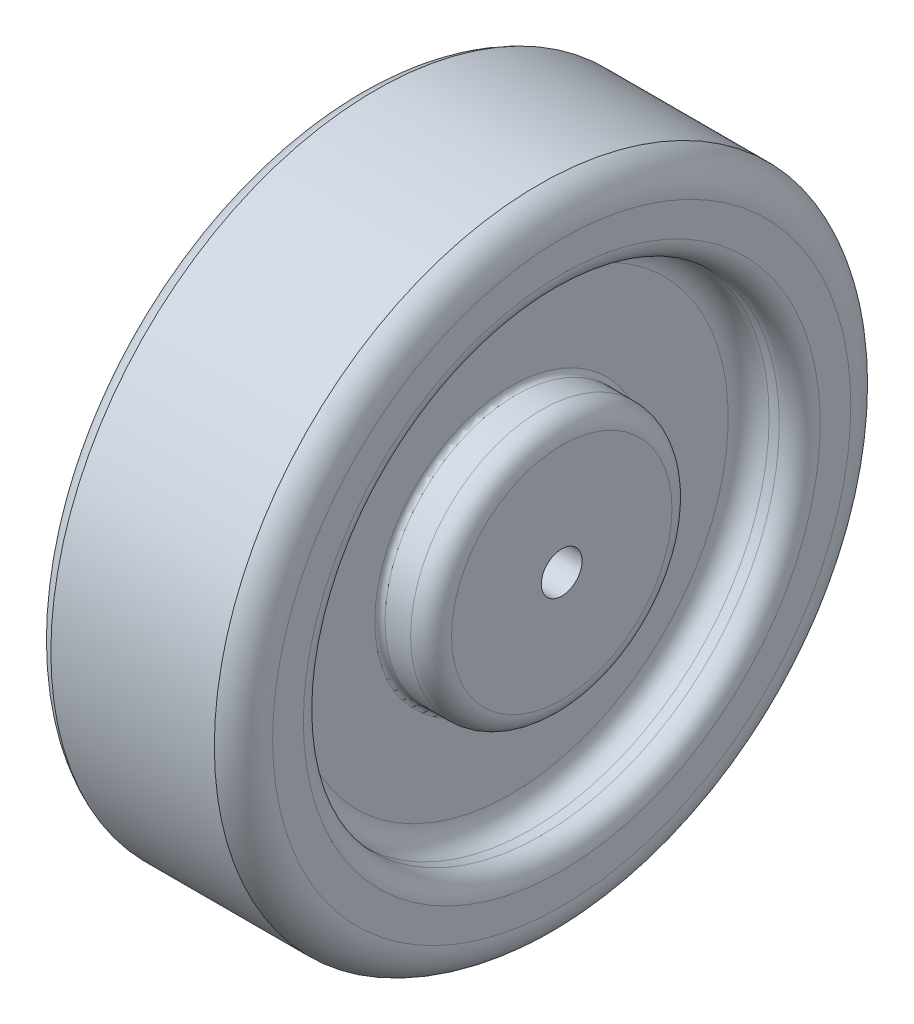
SolidWorks part; units mm, degrees
material "POLIURETANO RC (11671)"
ref_plane "Alzado" through (0, 0, 0) normal (0, 0, 1) x (1, 0, 0)
ref_plane "Planta" through (0, 0, 0) normal (0, 1, 0) x (1, 0, 0)
ref_plane "Vista lateral" through (0, 0, 0) normal (1, 0, 0) x (0, 0, -1)
sketch "Croquis3" plane through (0, 0, 0) normal (0, 1, 0) x (1, 0, 0)
  line L0 (20.5, 3.5822) -> (67.1331, 3.5822) construction
  line L1 (-20.5, 3.5822) -> (-65.0326, 3.5822) construction
  line L2 (-20.5, -2) -> (20.5, -2)
  line L3 (-20.5, 3.5822) -> (20.5, 3.5822) construction
  line L4 (-55, 0) -> (55, 0) construction
  line L6 (0, 3.5822) -> (0, -71.0271) construction
  line L7 (-20.5, -2) -> (-20.5, -17)
  line L8 (20.5, -48) -> (20.5, -47)
  line L9 (16.5, -43) -> (14.5, -43)
  line L10 (20.5, -17) -> (20.5, -18)
  line L11 (16.5, -22) -> (11.5, -22)
  line L12 (10.5, -23) -> (10.5, -39)
  line L14 (20.5, -2) -> (20.5, -17)
  line L15 (-10.5, -23) -> (-10.5, -39)
  line L16 (-16.5, -22) -> (-11.5, -22)
  line L17 (-20.5, -17) -> (-20.5, -18)
  line L18 (-16.5, -43) -> (-14.5, -43)
  line L19 (-20.5, -48) -> (-20.5, -47)
  line L20 (-20.5, -48) -> (-20.5, -53)
  line L22 (-16, -59.9178) -> (16, -59.9178)
  line L24 (20.5, -53) -> (20.5, -48)
  arc A0 (16.5, -43) -> (20.5, -47) centre (16.5, -47) cw
  arc A1 (10.5, -39) -> (14.5, -43) centre (14.5, -39) ccw
  arc A2 (11.5, -22) -> (10.5, -23) centre (11.5, -23) ccw
  arc A3 (20.5, -18) -> (16.5, -22) centre (16.5, -18) cw
  arc A4 (-20.5, -18) -> (-16.5, -22) centre (-16.5, -18) ccw
  arc A5 (-11.5, -22) -> (-10.5, -23) centre (-11.5, -23) cw
  arc A6 (-10.5, -39) -> (-14.5, -43) centre (-14.5, -39) cw
  arc A7 (-16.5, -43) -> (-20.5, -47) centre (-16.5, -47) ccw
  arc A8 (-16, -59.9178) -> (-20.5, -53) centre (-13.5101, -53.3756) cw
  arc A9 (16, -59.9178) -> (20.5, -53) centre (13.5101, -53.3756) ccw
  point P7 (0, -4)
  point P13 (0, -50)
  point P17 (0, -19)
  point P23 (20.5, -43)
  point P26 (10.5, -43)
  point P31 (-10.5, -43)
  point P32 (0, -2)
  point P45 (0, -50)
  point P46 (-20.5, -43)
  point P56 (0, -59.9178)
  dimension "D9" = 4
  dimension "D10" = 4
  dimension "D11" = 1
  dimension "D12" = 4
  dimension "D2" = 2
  dimension "D3" = 5
  dimension "D4" = 63.5
  dimension "D5" = 15
  dimension "D6" = 1
  dimension "D7" = 5
  dimension "D8" = 10
  dimension "D13" = 5
revolve "Revolución1" add sketch "Croquis3" angle 360 about L3
sketch "Croquis4" plane through (-20.5, 0, 0) normal (-1, 0, 0) x (0, 0, 1)
  circle A0 centre (-3.5822, 0) radius 5.5822
  circle A1 centre (-3.5822, 0) radius 4
extrude "Saliente-Extruir1" add sketch "Croquis4" against normal blind 41
sketch "Croquis5" plane through (0, 0, 0) normal (1, 0, 0) x (0, 0, -1)
  line L1 (-2.5457, -63.7964) -> (9.7101, -63.7964)
  line L2 (-2.5457, -63.7964) -> (-2.5457, -63.2036)
  line L3 (-2.5457, -63.2036) -> (9.7101, -63.2036)
  line L4 (9.7101, -63.7964) -> (9.7101, -63.2036)
  line L5 (-2.5457, -63.7964) -> (9.7101, -63.2036) construction
  line L6 (-2.5457, -63.2036) -> (9.7101, -63.7964) construction
  circle A0 centre (3.5822, 0) radius 63.5 construction
  point P0 (3.5822, -63.5)
extrude "Cortar-Extruir1" cut sketch "Croquis5" along normal mid plane 87
